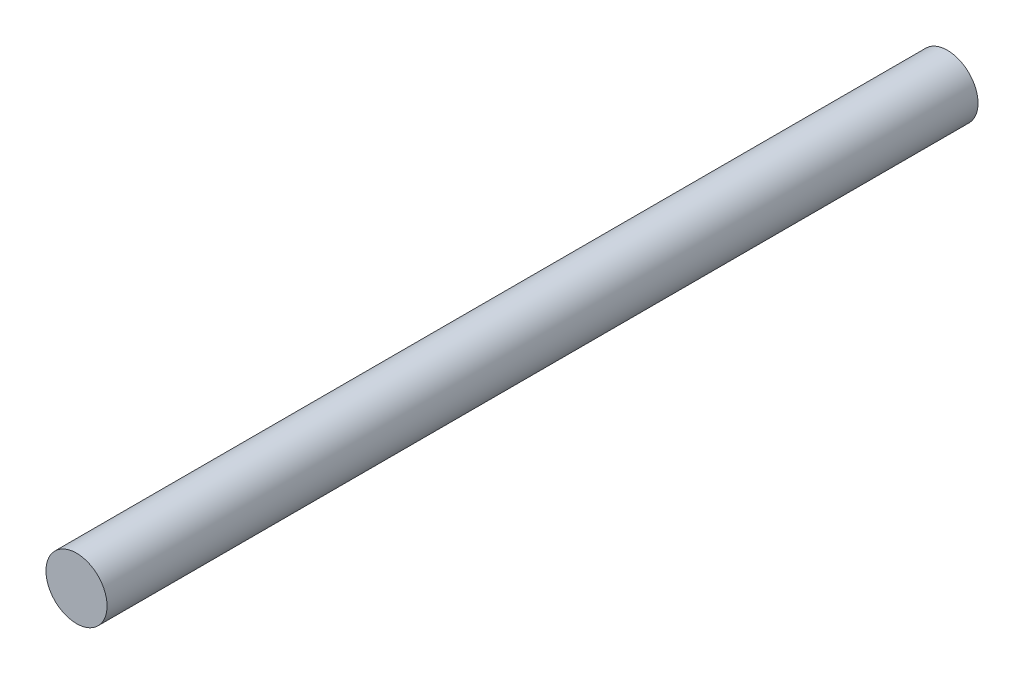
SolidWorks part; units mm, degrees
ref_plane "Front Plane" through (0, 0, 0) normal (0, 0, 1) x (1, 0, 0)
ref_plane "Top Plane" through (0, 0, 0) normal (0, 1, 0) x (1, 0, 0)
ref_plane "Right Plane" through (0, 0, 0) normal (1, 0, 0) x (0, 0, -1)
sketch "Sketch1" plane through (0, 0, 0) normal (0, 0, 1) x (1, 0, 0)
  circle A0 centre (0, 0) radius 2.54
  dimension "D1" = 5.08
extrude "Boss-Extrude1" add sketch "Sketch1" along normal blind 72.39
